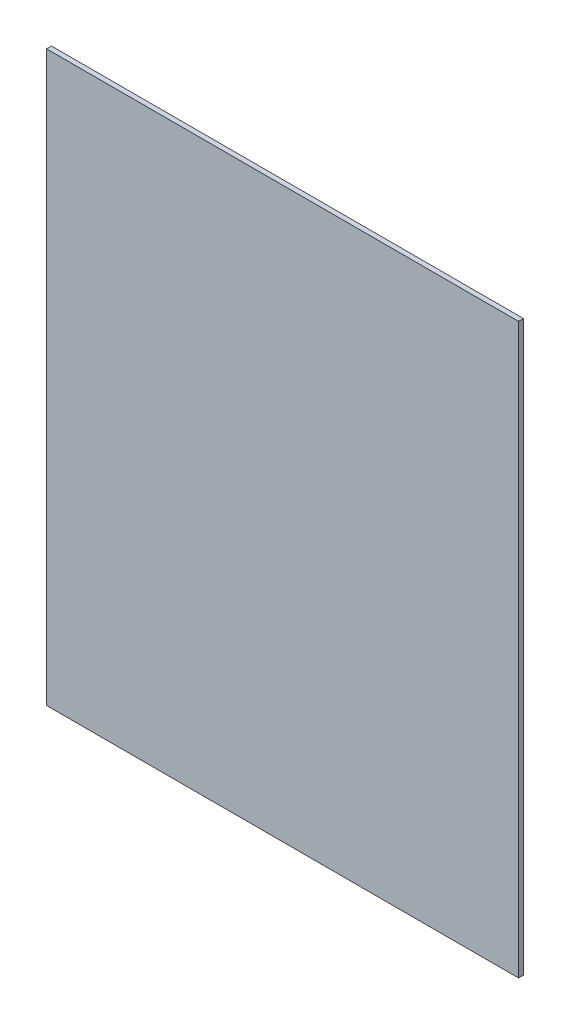
SolidWorks part; units mm, degrees
ref_plane "Plan de face" through (0, 0, 0) normal (0, 0, 1) x (1, 0, 0)
ref_plane "Plan de dessus" through (0, 0, 0) normal (0, 1, 0) x (1, 0, 0)
ref_plane "Plan de droite" through (0, 0, 0) normal (1, 0, 0) x (0, 0, -1)
sketch "Esquisse1" plane through (0, 0, 0) normal (0, 0, 1) x (1, 0, 0)
  line L1 (-312.5, -376.5) -> (312.5, -376.5)
  line L2 (-312.5, -376.5) -> (-312.5, 376.5)
  line L3 (-312.5, 376.5) -> (312.5, 376.5)
  line L4 (312.5, -376.5) -> (312.5, 376.5)
  line L5 (-312.5, -376.5) -> (312.5, 376.5) construction
  line L6 (-312.5, 376.5) -> (312.5, -376.5) construction
  point P0 (0, 0)
  dimension "D1" = 753
  dimension "D2" = 625
extrude "Boss.-Extru.1" add sketch "Esquisse1" along normal blind 6.5
